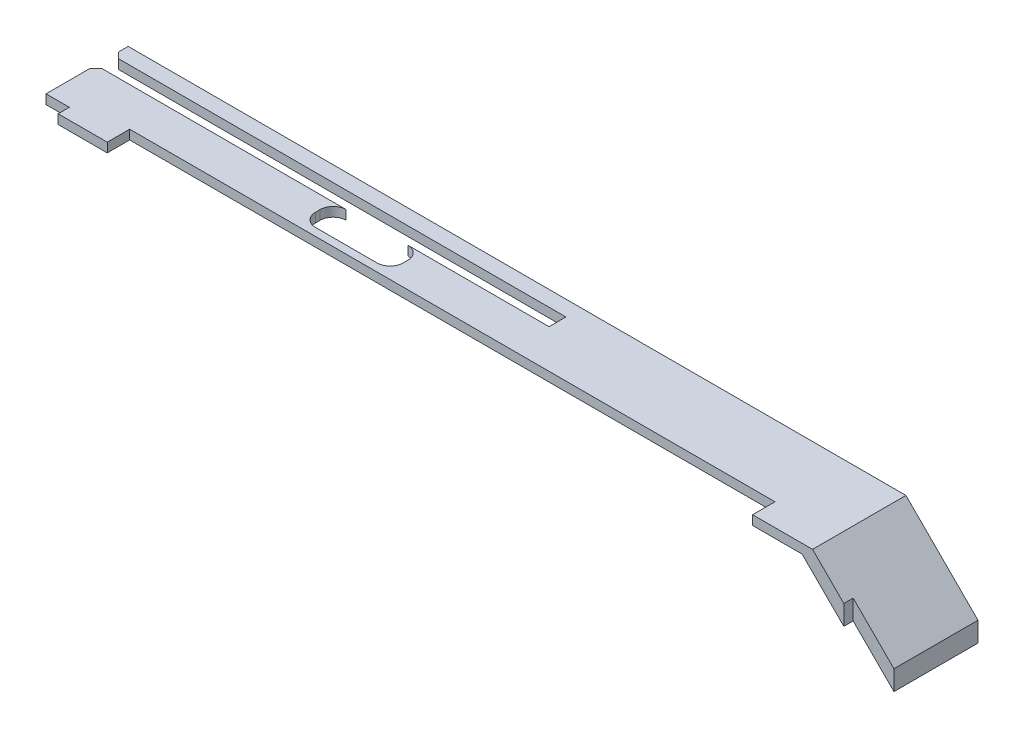
SolidWorks part; units mm, degrees
ref_plane "前视基准面" through (0, 0, 0) normal (0, 0, 1) x (1, 0, 0)
ref_plane "上视基准面" through (0, 0, 0) normal (0, 1, 0) x (1, 0, 0)
ref_plane "右视基准面" through (0, 0, 0) normal (1, 0, 0) x (0, 0, -1)
other "Configuration Table"
sketch "草图1" plane through (0, 0, 0) normal (0, 1, 0) x (1, 0, 0)
  line L0 (-14.6359, 19.4062) -> (-14.6359, 10.6062)
  line L1 (-14.6359, 10.6062) -> (-12.1359, 10.6062)
  line L2 (-12.1359, 10.6062) -> (-12.1359, 9.4062)
  line L3 (-12.1359, 9.4062) -> (71.9965, 9.4062)
  line L4 (71.9965, 9.4062) -> (71.9965, 10.4062)
  line L5 (71.9965, 10.4062) -> (76.3641, 10.4062)
  line L6 (76.3641, 10.4062) -> (76.3641, 19.4063)
  line L7 (76.3641, 19.4063) -> (-14.6359, 19.4062)
  dimension "D1" = 8.8
  dimension "D2" = 1.2
  dimension "D3" = 2.5
  dimension "D4" = 4.3675
  dimension "D5" = 1
  dimension "D6" = 91
extrude "凸台-拉伸1" add sketch "草图1" along normal blind 10
sketch "草图2" plane through (0, 0, -9.4062) normal (0, 0, 1) x (1, 0, 0)
  line L0 (-14.6359, 9) -> (67.5267, 9)
  line L1 (-14.6359, 10) -> (-14.6359, 0) construction
  line L2 (67.5267, 9) -> (76.5267, 0)
  line L3 (-12.1359, 0) -> (71.9965, 0) construction
  line L4 (-14.6359, 9) -> (-14.6359, 0)
  line L5 (-14.6359, 0) -> (76.5267, 0)
  line L6 (78.3326, 0.3154) -> (67.4307, 11.2173)
  line L7 (67.4307, 11.2173) -> (78.3936, 11.2173)
  line L8 (78.3936, 11.2173) -> (78.3326, 0.3154)
  line L9 (-14.6359, 10) -> (68.6481, 10) construction
  line L10 (-12.1359, 10) -> (71.9965, 10) construction
  dimension "D1" = 83.284
  dimension "D2" = 135
  dimension "D3" = 1.5
  dimension "D4" = 2
extrude "切除-拉伸1" cut sketch "草图2" against normal through all
sketch "草图3" plane through (0, 10, 0) normal (0, 1, 0) x (1, 0, 0)
  line L0 (-14.6359, 19.4062) -> (-14.6359, 10.6062) construction
  line L1 (-14.6359, 17.7463) -> (33.8941, 17.7463)
  line L2 (-14.6359, 17.7463) -> (-14.6359, 15.9463)
  line L3 (-14.6359, 15.9463) -> (33.8941, 15.9463)
  line L4 (33.8941, 17.7463) -> (33.8941, 15.9463)
  line L5 (68.6481, 19.4063) -> (-14.6359, 19.4062) construction
  line L6 (-12.1359, 9.4062) -> (68.6481, 9.4062) construction
  line L7 (-6.8759, 9.4062) -> (62.2241, 9.4062)
  line L8 (-6.8759, 9.4062) -> (-6.8759, 11.8062)
  line L9 (-6.8759, 11.8062) -> (62.2241, 11.8062)
  line L10 (62.2241, 9.4062) -> (62.2241, 11.8062)
  line L11 (-12.1359, 10.6062) -> (-12.1359, 9.4062) construction
  dimension "D1" = 1.8
  dimension "D2" = 1.66
  dimension "D3" = 48.53
  dimension "D4" = 5.26
  dimension "D5" = 2.4
  dimension "D6" = 69.1
extrude "切除-拉伸2" cut sketch "草图3" against normal through all
sketch "草图4" plane through (0, 10, 0) normal (0, 1, 0) x (1, 0, 0)
  line L0 (-14.6359, 15.9463) -> (33.8941, 15.9463) construction
  line L4 (12.17, 15.9463) -> (18.77, 15.9463)
  line L5 (10.77, 14.5463) -> (10.77, 14.048)
  line L6 (12.17, 12.648) -> (18.77, 12.648)
  line L7 (20.17, 14.5463) -> (20.17, 14.048)
  arc A2 (12.17, 15.9463) -> (10.77, 14.5463) centre (12.17, 14.5463) ccw
  arc A3 (10.77, 14.048) -> (12.17, 12.648) centre (12.17, 14.048) ccw
  arc A4 (18.77, 12.648) -> (20.17, 14.048) centre (18.77, 14.048) ccw
  arc A5 (18.77, 15.9463) -> (20.17, 14.5463) centre (18.77, 14.5463) cw
  point P8 (10.77, 15.9463)
  point P11 (10.77, 12.648)
  point P14 (20.17, 12.648)
  dimension "D2" = 1.4
  dimension "D1" = 9.4
  dimension "D3" = 3.2982
extrude "切除-拉伸3" cut sketch "草图4" against normal through all
chamfer "倒角1" distance 0.6 angle 45 2 edges at (-14.6359, 9.5, -17.7463) (-14.6359, 9.5, -15.9463)
